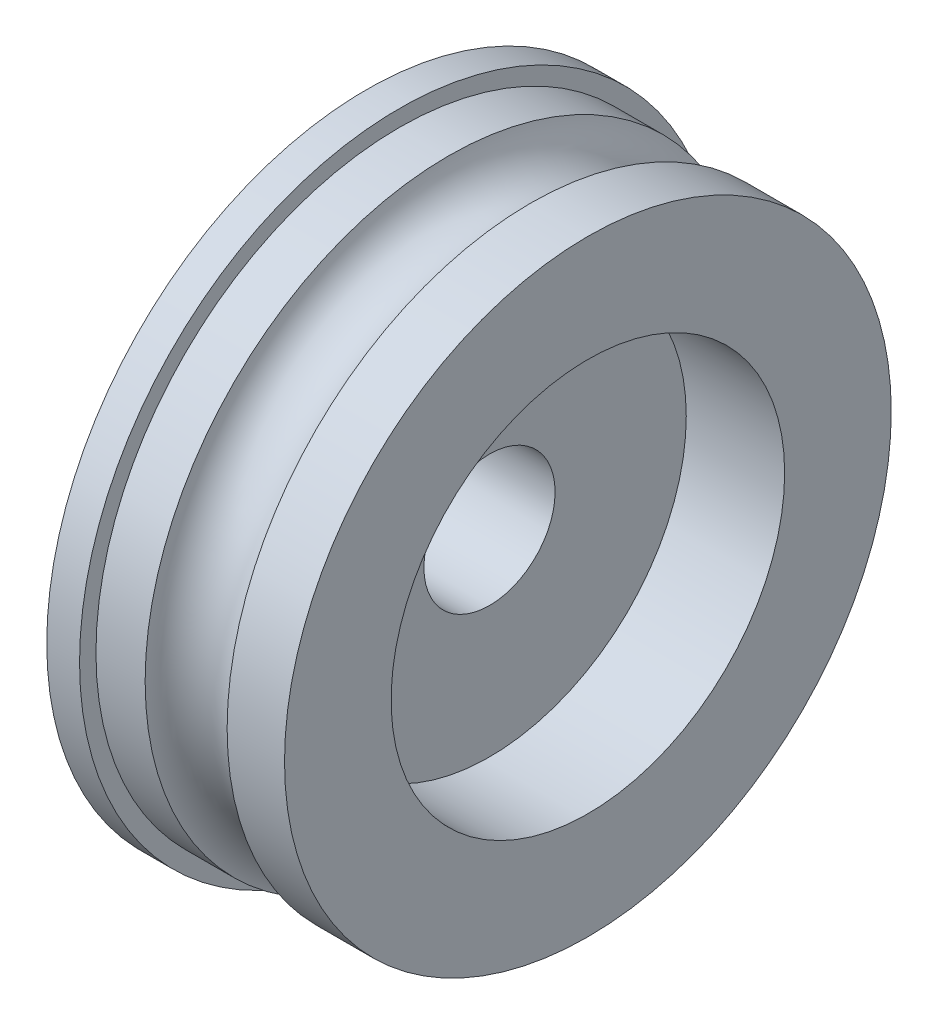
SolidWorks part; units mm, degrees
ref_plane "Front Plane" through (0, 0, 0) normal (0, 0, 1) x (1, 0, 0)
ref_plane "Top Plane" through (0, 0, 0) normal (0, 1, 0) x (1, 0, 0)
ref_plane "Right Plane" through (0, 0, 0) normal (1, 0, 0) x (0, 0, -1)
sketch "Sketch1" plane through (0, 0, 0) normal (0, 1, 0) x (1, 0, 0)
  line L0 (-3.4904, 9.75) -> (-2.4904, 9.75)
  line L1 (-2.4904, 9.75) -> (-2.4904, 9.25)
  line L2 (-2.4904, 9.25) -> (-0.9904, 9.25)
  line L3 (1.5096, 9.25) -> (3.2596, 9.25)
  line L4 (3.2596, 9.25) -> (3.2596, 2)
  line L5 (3.2596, 2) -> (-3.4904, 2)
  line L6 (-3.4904, 2) -> (-3.4904, 9.75)
  line L7 (-2.7281, 0) -> (1.5096, 0) construction
  arc A0 (-0.9904, 9.25) -> (1.5096, 9.25) centre (0.2596, 9.5) ccw
  dimension "D1" = 1
  dimension "D2" = 3
  dimension "D3" = 2
  dimension "D4" = 1.5
  dimension "D5" = 9.75
  dimension "D6" = 9.25
  dimension "D7" = 9.25
  dimension "D8" = 9.5
revolve "Revolve1" add sketch "Sketch1" angle 360 about L7
sketch "Sketch2" plane through (3.2596, 0, 0) normal (1, 0, 0) x (0, 0, -1)
  circle A0 centre (0, 0) radius 6
  dimension "D1" = 12
extrude "Cut-Extrude1" cut sketch "Sketch2" against normal blind 3
